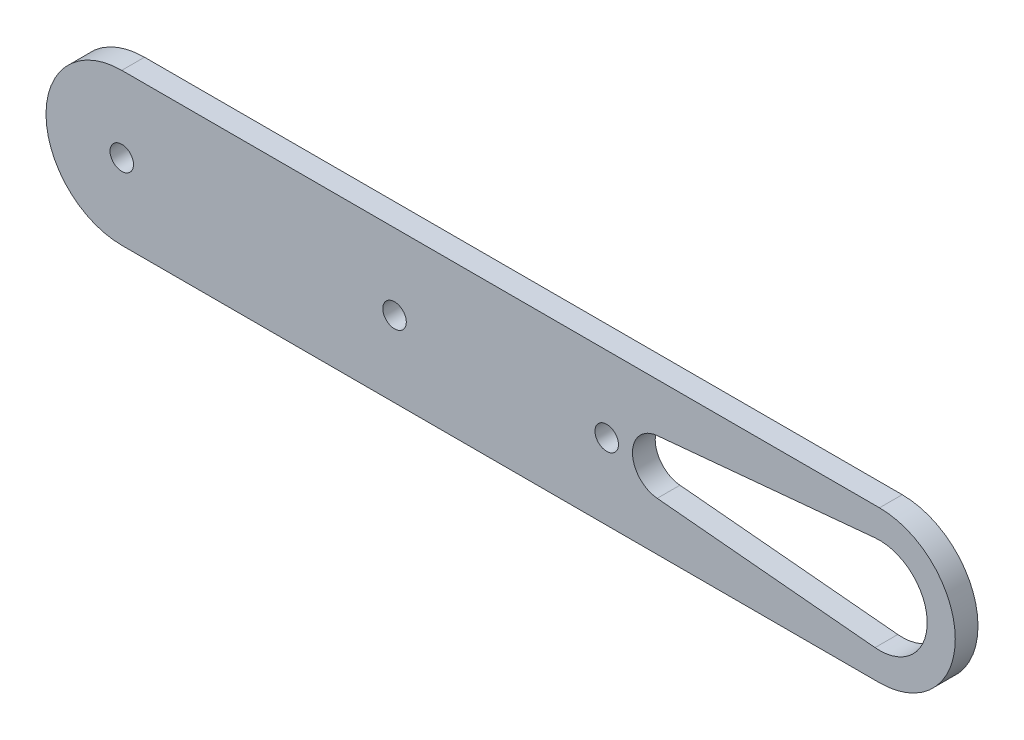
SolidWorks part; units mm, degrees
ref_plane "Front Plane" through (0, 0, 0) normal (0, 0, 1) x (1, 0, 0)
ref_plane "Top Plane" through (0, 0, 0) normal (0, 1, 0) x (1, 0, 0)
ref_plane "Right Plane" through (0, 0, 0) normal (1, 0, 0) x (0, 0, -1)
sketch "Sketch1" plane through (0, 0, 0) normal (0, 0, 1) x (1, 0, 0)
  line L0 (-58.0586, 14.1911) -> (41.9414, 14.1911) construction
  line L1 (-58.0586, 24.1911) -> (41.9414, 24.1911)
  line L2 (-58.0586, 4.1911) -> (41.9414, 4.1911)
  arc A0 (-58.0586, 24.1911) -> (-58.0586, 4.1911) centre (-58.0586, 14.1911) ccw
  arc A1 (41.9414, 4.1911) -> (41.9414, 24.1911) centre (41.9414, 14.1911) ccw
  point P2 (-8.0586, 14.1911)
extrude "Boss-Extrude1" add sketch "Sketch1" along normal blind 3
sketch "Sketch3" plane through (0, 0, 3) normal (0, 0, 1) x (1, 0, 0)
  circle A0 centre (-58.0586, 14.1911) radius 1.55
  arc A1 (-58.0586, 24.1911) -> (-58.0586, 4.1911) centre (-58.0586, 14.1911) ccw construction
extrude "Cut-Extrude2" cut sketch "Sketch3" against normal blind 3 contours A0
sketch "Sketch4" plane through (9.9795, 1.4333, 3) normal (0, 0, 1) x (1, 0, 0)
  line L0 (-68.0381, 2.7578) -> (31.9619, 2.7578) construction
  circle A0 centre (-4.0381, 12.7578) radius 1.55
  arc A2 (31.9619, 2.7578) -> (31.9619, 22.7578) centre (31.9619, 12.7578) ccw construction
  dimension "D1" = 10
  dimension "D2" = 36
extrude "Cut-Extrude4" cut sketch "Sketch4" against normal blind 3
sketch "Sketch5" plane through (-9.9795, 1.4333, 0) normal (0, 0, -1) x (-1, 0, 0)
  line L0 (-51.9208, 22.7578) -> (48.0792, 22.7578) construction
  circle A0 centre (12.0792, 12.7578) radius 1.55
  arc A2 (48.0792, 2.7578) -> (48.0792, 22.7578) centre (48.0792, 12.7578) ccw construction
  dimension "D1" = 10
  dimension "D2" = 36
extrude "Cut-Extrude6" cut sketch "Sketch5" against normal blind 3
sketch "Sketch6" plane through (0, 0, 3) normal (0, 0, 1) x (1, 0, 0)
  line L0 (12.6062, 17.7755) -> (41.3548, 20.4637)
  line L1 (41.3548, 7.9185) -> (12.6062, 10.6067)
  arc A0 (41.3548, 20.4637) -> (41.3548, 7.9185) centre (41.9414, 14.1911) cw
  arc A1 (12.6062, 10.6067) -> (12.6062, 17.7755) centre (12.9414, 14.1911) cw
  arc A2 (41.9414, 4.1911) -> (41.9414, 24.1911) centre (41.9414, 14.1911) ccw construction
  point P14 (9.3414, 14.1911)
  point P15 (48.2414, 14.1911)
  dimension "D1" = 6.3
  dimension "D3" = 3.6
  dimension "D2" = 38.9
extrude "Cut-Extrude7" cut sketch "Sketch6" against normal blind 3
